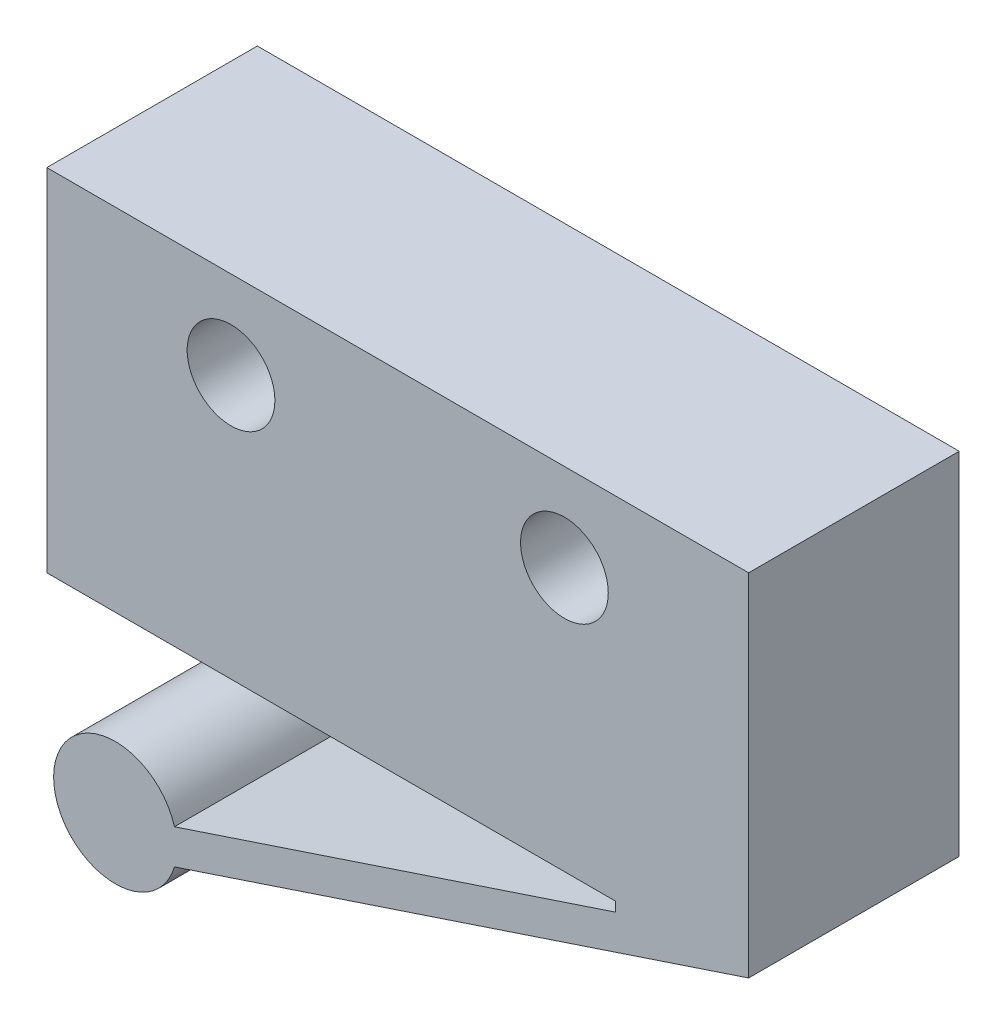
SolidWorks part; units mm, degrees
ref_plane "Plan de face" through (0, 0, 0) normal (0, 0, 1) x (1, 0, 0)
ref_plane "Plan de dessus" through (0, 0, 0) normal (0, 1, 0) x (1, 0, 0)
ref_plane "Plan de droite" through (0, 0, 0) normal (1, 0, 0) x (0, 0, -1)
sketch "Esquisse1" plane through (0, 0, 0) normal (0, 0, 1) x (1, 0, 0)
  line L0 (0, 0) -> (-20, 0)
  line L1 (-20, 0) -> (-20, -10)
  line L2 (-20, -10) -> (-3.7932, -10)
  line L3 (-3.7932, -10) -> (-3.7932, -10.271)
  line L4 (-3.7932, -10.271) -> (-16.3617, -14.4487)
  line L5 (0, 0) -> (0, -10)
  line L6 (-16.362, -15.4386) -> (0, -10)
  arc A0 (-16.3617, -14.4487) -> (-16.362, -15.4386) centre (-18.0482, -14.9432) ccw
  circle A1 centre (-14.75, -2.5) radius 1.25
  circle A2 centre (-5.25, -2.5) radius 1.25
  dimension "D5" = 2.5
  dimension "D6" = 2.5
  dimension "D1" = 20
  dimension "D2" = 10
  dimension "D3" = 10
  dimension "D4" = 2.5
  dimension "D7" = 2.5
  dimension "D8" = 9.5
  dimension "D9" = 5.25
extrude "Boss.-Extru.1" add sketch "Esquisse1" along normal blind 6
